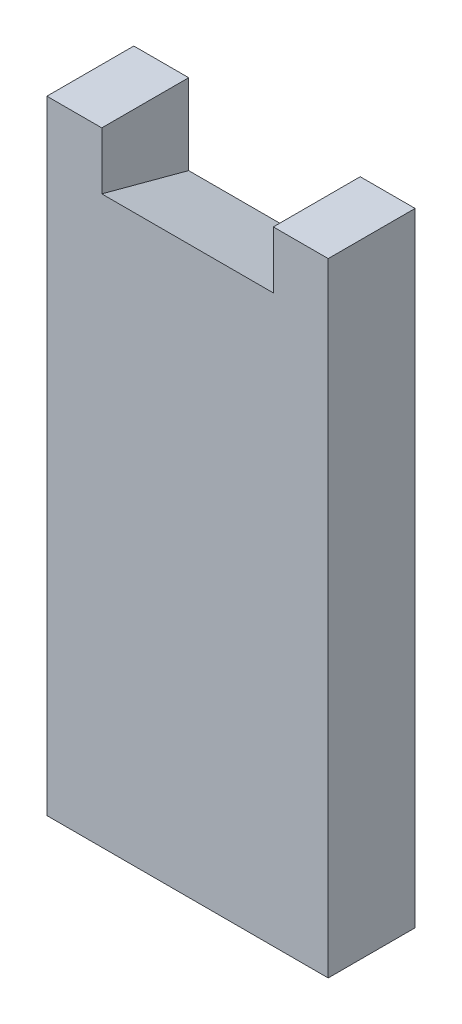
SolidWorks part; units mm, degrees
ref_plane "前视基准面" through (0, 0, 0) normal (0, 0, 1) x (1, 0, 0)
ref_plane "上视基准面" through (0, 0, 0) normal (0, 1, 0) x (1, 0, 0)
ref_plane "右视基准面" through (0, 0, 0) normal (1, 0, 0) x (0, 0, -1)
sketch "草图1" plane through (0, 0, 0) normal (0, 0, 1) x (1, 0, 0)
  line L1 (0, 0) -> (24.6, 0)
  line L2 (0, 0) -> (0, -54.485)
  line L3 (0, -54.485) -> (24.6, -54.485)
  line L4 (24.6, 0) -> (24.6, -54.485)
  line L5 (4.8, 0) -> (19.8, 0)
  line L6 (4.8, 0) -> (4.8, -5)
  line L7 (4.8, -5) -> (19.8, -5)
  line L8 (19.8, 0) -> (19.8, -5)
  point P9 (12.3, 0)
  dimension "D1" = 5
  dimension "D2" = 24.6
  dimension "D3" = 15
  dimension "D4" = 49.485
extrude "凸台-拉伸1" add sketch "草图1" along normal blind 7.6 contours L1 L8 L7 L6 L2 L3 L4
draft "拔模5" type of draft neutral plane draft angle 15 faces to draft 1 face at (12.3, -5, 3.8) neutral plane through (0, 0, 7.6) neutral plane normal (0, 0, 1) reverse direction yes parameters "D1"=15
